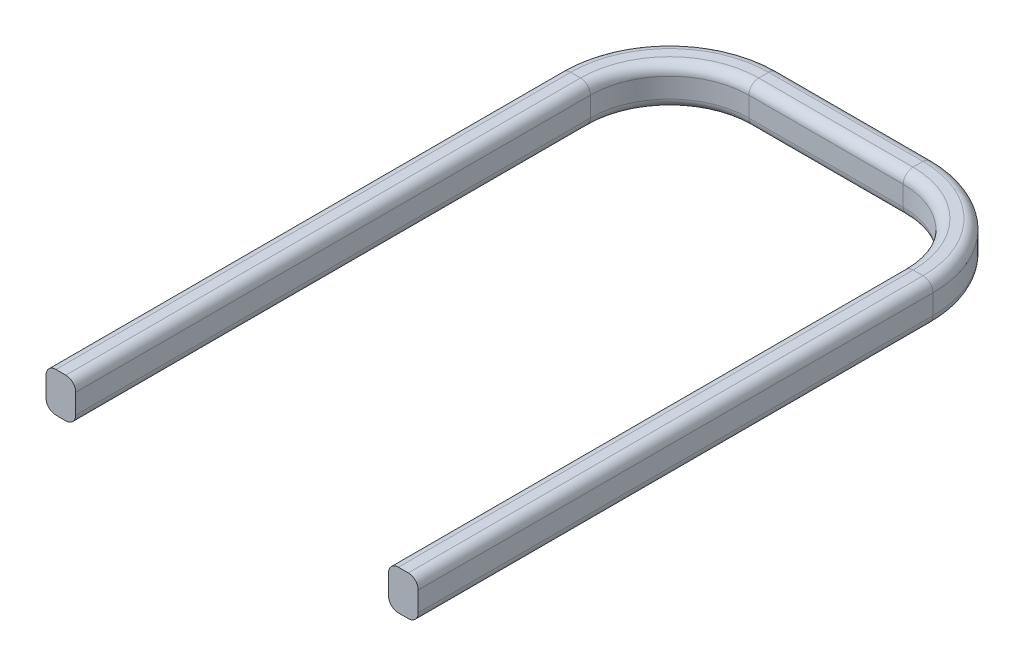
SolidWorks part; units mm, degrees
ref_plane "前视基准面" through (0, 0, 0) normal (0, 0, 1) x (1, 0, 0)
ref_plane "上视基准面" through (0, 0, 0) normal (0, 1, 0) x (1, 0, 0)
ref_plane "右视基准面" through (0, 0, 0) normal (1, 0, 0) x (0, 0, -1)
sketch "草图3" plane through (0, 0, 0) normal (0, 1, 0) x (1, 0, 0)
  line L0 (-3.95, 0) -> (-3.95, 13)
  line L1 (-1.95, 15) -> (1.95, 15)
  line L2 (3.95, 13) -> (3.95, 0)
  line L3 (0, 0) -> (0, 19.2925) construction
  arc A0 (1.95, 15) -> (3.95, 13) centre (1.95, 13) cw
  arc A1 (-3.95, 13) -> (-1.95, 15) centre (-1.95, 13) cw
  point P11 (-3.95, 15)
  point P12 (0, 0)
  dimension "D3" = 2
  dimension "D1" = 3.95
  dimension "D2" = 15
sketch "草图5" plane through (0, 0, 0) normal (0, 0, 1) x (1, 0, 0)
  line L1 (-3.95, 0) -> (-4.7, 0)
  line L2 (-3.95, 0) -> (-3.95, 1)
  line L3 (-3.95, 1) -> (-4.7, 1)
  line L4 (-4.7, 0) -> (-4.7, 1)
  dimension "D1" = 1
  dimension "D2" = 0.75
sweep "扫描1" add profiles "草图5" path "草图3"
fillet "圆角1" radius 0.25 20 edges at (4.7, 0, -6.5) (3.8945, 0, -14.9445) (0, 0, -15.75) (-3.8945, 0, -14.9445) (4.7, 1, -6.5) (3.8945, 1, -14.9445) (0, 1, -15.75) (-3.8945, 1, -14.9445) (3.95, 0, -6.5) (3.3642, 0, -14.4142) (0, 0, -15) (-3.3642, 0, -14.4142) (3.95, 1, -6.5) (3.3642, 1, -14.4142) (0, 1, -15) (-3.3642, 1, -14.4142) (-4.7, 0, -6.5) (-4.7, 1, -6.5) (-3.95, 0, -6.5) (-3.95, 1, -6.5)
